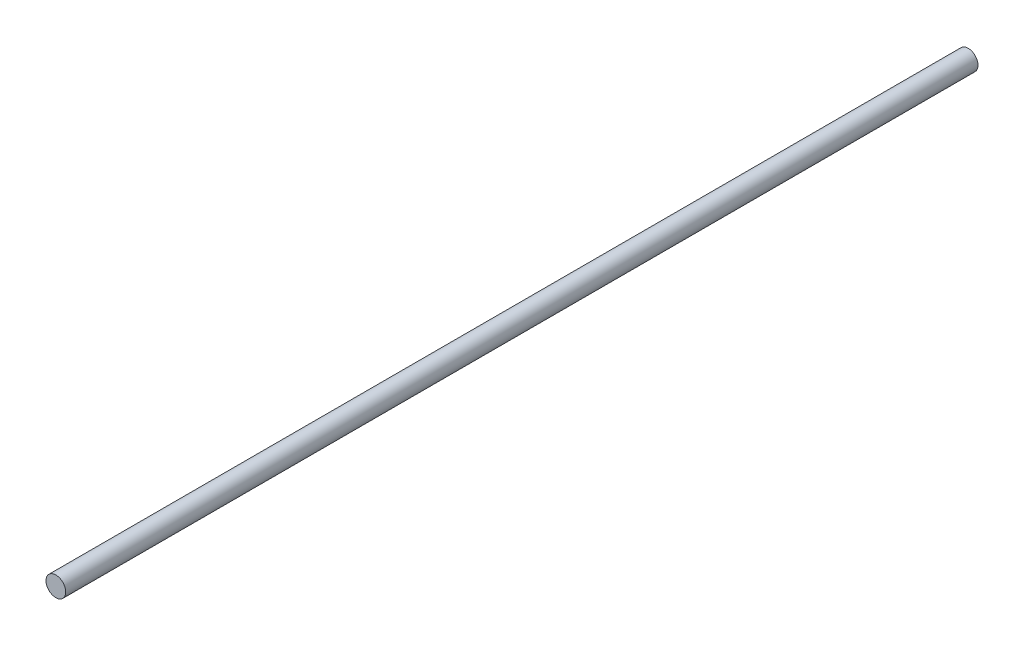
SolidWorks part; units mm, degrees
ref_plane "前视基准面" through (0, 0, 0) normal (0, 0, 1) x (1, 0, 0)
ref_plane "上视基准面" through (0, 0, 0) normal (0, 1, 0) x (1, 0, 0)
ref_plane "右视基准面" through (0, 0, 0) normal (1, 0, 0) x (0, 0, -1)
sketch "草图1" plane through (0, 0, 0) normal (0, 0, 1) x (1, 0, 0)
  circle A0 centre (0, 0) radius 4
  dimension "D1" = 8
extrude "凸台-拉伸1" add sketch "草图1" against normal blind 370
